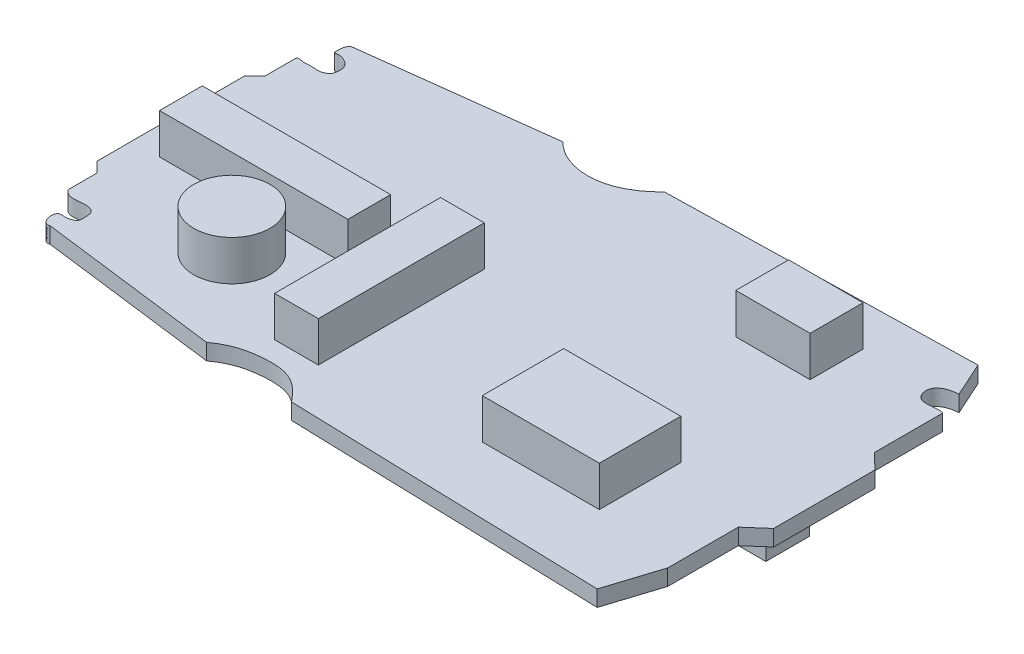
SolidWorks part; units mm, degrees
ref_plane "前视基准面" through (0, 0, 0) normal (0, 0, 1) x (1, 0, 0)
ref_plane "上视基准面" through (0, 0, 0) normal (0, 1, 0) x (1, 0, 0)
ref_plane "右视基准面" through (0, 0, 0) normal (1, 0, 0) x (0, 0, -1)
other "Configuration Table"
sketch "草图1" plane through (0, 0, 0) normal (0, 1, 0) x (1, 0, 0)
  line L0 (257.3444, 580.9538) -> (1286.7218, 580.9538) construction
  line L1 (26.5422, 34.285) -> (26.5422, 23.2356)
  line L2 (75.5422, 32.3301) -> (75.5422, 24.7655)
  line L3 (49.3636, 14.9485) -> (72.8649, 14.2685)
  line L4 (28.9646, 17.3284) -> (42.3514, 15.6285)
  line L5 (28.6246, 40.1497) -> (42.6914, 41.8921)
  line L6 (49.7036, 42.4446) -> (72.6099, 42.9546)
  line L7 (74.3948, 38.5348) -> (74.3948, 33.4351)
  line L8 (74.3948, 33.4351) -> (75.5422, 32.3301)
  line L9 (74.1398, 18.2633) -> (74.1398, 23.5331)
  line L10 (74.1398, 23.5331) -> (75.5422, 24.7655)
  line L11 (74.1398, 18.2633) -> (72.8649, 14.2685)
  line L12 (27.3072, 20.3457) -> (27.3072, 22.4706)
  line L13 (27.3072, 22.4706) -> (26.5422, 23.2356)
  line L14 (26.5422, 34.285) -> (27.3072, 35.05)
  line L15 (27.3072, 35.05) -> (27.3072, 37.2599)
  line L16 (72.6099, 42.9546) -> (73.7832, 40.3589)
  spline S0 degree 3 poles (27.3072, 20.3457) (27.7664, 19.7105) (28.5332, 20.1757) (29.7076, 19.8563) (29.7087, 19.2126) (29.7499, 18.6978) (29.3321, 18.4995) (28.9721, 18.4166) (28.0915, 18.5915) (28.3962, 17.1099) (28.9646, 17.3284) knots 0 0 0 0 0.289961 0.402398 0.499467 0.579199 0.625292 0.705975 0.770289 1 1 1 1
  spline S1 degree 3 poles (27.3072, 37.2599) (27.3146, 37.5218) (27.8307, 37.2925) (28.3534, 37.4371) (28.8764, 37.3142) (29.3186, 37.4353) (29.643, 37.6165) (29.7379, 37.9995) (29.7553, 38.3647) (29.5978, 38.7536) (29.3032, 38.9786) (28.9519, 39.1311) (28.6817, 39.1658) (28.3111, 39.1048) (28.3819, 39.3793) (28.3497, 39.7051) (28.4369, 40.0188) (28.6246, 40.1497) knots 0 0 0 0 0.103746 0.179481 0.291749 0.356069 0.410238 0.467474 0.543083 0.593547 0.671678 0.723594 0.780978 0.824017 0.858913 0.887994 1 1 1 1
  spline S2 degree 3 poles (42.6914, 41.8921) (43.7098, 40.8164) (46.5553, 40.1214) (48.9061, 41.5984) (49.7036, 42.4446) knots 0 0 0 0 0.550222 1 1 1 1
  spline S3 degree 3 poles (42.3514, 15.6285) (43.2994, 16.3706) (45.0807, 16.8346) (47.8221, 16.7063) (48.8882, 15.5368) (49.3636, 14.9485) knots 0 0 0 0 0.44565 0.701197 1 1 1 1
  spline S4 degree 3 poles (74.3948, 38.5348) (74.009, 38.7554) (72.5557, 38.0853) (72.069, 40.0639) (73.3453, 40.3582) (73.7832, 40.3589) knots 0 0 0 0 0.405658 0.627639 1 1 1 1
  dimension "D1" = 49
extrude "凸台-拉伸1" add sketch "草图1" along normal blind 1.2
sketch "草图2" plane through (0, 1.2, 0) normal (0, 1, 0) x (1, 0, 0)
  line L1 (59.0791, 25.5574) -> (67.8191, 25.5574)
  line L2 (59.0791, 25.5574) -> (59.0791, 19.4774)
  line L3 (59.0791, 19.4774) -> (67.8191, 19.4774)
  line L4 (67.8191, 25.5574) -> (67.8191, 19.4774)
  line L5 (61.7391, 39.6934) -> (67.2871, 39.6934)
  line L6 (61.7391, 39.6934) -> (61.7391, 35.7414)
  line L7 (61.7391, 35.7414) -> (67.2871, 35.7414)
  line L8 (67.2871, 39.6934) -> (67.2871, 35.7414)
  line L9 (28.6032, 29.0534) -> (42.6632, 29.0534)
  line L10 (28.6032, 29.0534) -> (28.6032, 25.8614)
  line L11 (28.6032, 25.8614) -> (42.6632, 25.8614)
  line L12 (42.6632, 29.0534) -> (42.6632, 25.8614)
  line L13 (47.9832, 18.3374) -> (44.7152, 18.3374)
  line L14 (47.9832, 18.3374) -> (47.9832, 30.7254)
  line L15 (47.9832, 30.7254) -> (44.7152, 30.7254)
  line L16 (44.7152, 18.3374) -> (44.7152, 30.7254)
  circle A0 centre (37.4952, 22.3654) radius 2.8457
extrude "凸台-拉伸2" add sketch "草图2" along normal blind 3
sketch "草图3" plane through (0, 0, 0) normal (0, -1, 0) x (-1, 0, 0)
  line L1 (-29.695, 26.0346) -> (-32.3787, 26.0346)
  line L2 (-29.695, 26.0346) -> (-29.695, 29.2874)
  line L3 (-29.695, 29.2874) -> (-32.3787, 29.2874)
  line L4 (-32.3787, 26.0346) -> (-32.3787, 29.2874)
  line L5 (-50.432, 26.0346) -> (-53.2783, 26.0346)
  line L6 (-50.432, 26.0346) -> (-50.432, 29.2874)
  line L7 (-50.432, 29.2874) -> (-53.2783, 29.2874)
  line L8 (-53.2783, 26.0346) -> (-53.2783, 29.2874)
  line L9 (-70.681, 26.0346) -> (-73.6899, 26.0346)
  line L10 (-70.681, 26.0346) -> (-70.681, 29.2874)
  line L11 (-70.681, 29.2874) -> (-73.6899, 29.2874)
  line L12 (-73.6899, 26.0346) -> (-73.6899, 29.2874)
extrude "凸台-拉伸3" add sketch "草图3" along normal blind 2.5
